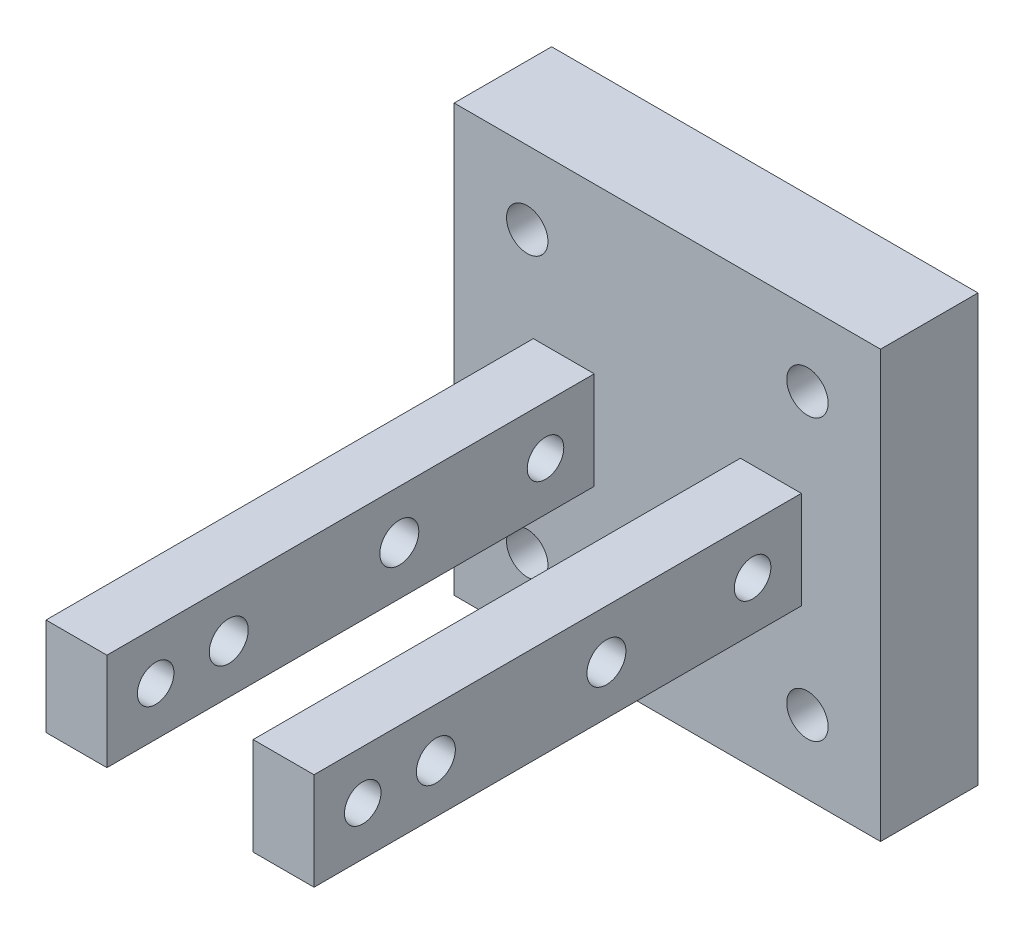
SolidWorks part; units mm, degrees
ref_plane "前视基准面" through (0, 0, 0) normal (0, 0, 1) x (1, 0, 0)
ref_plane "上视基准面" through (0, 0, 0) normal (0, 1, 0) x (1, 0, 0)
ref_plane "右视基准面" through (0, 0, 0) normal (1, 0, 0) x (0, 0, -1)
sketch "草图1" plane through (0, 0, 0) normal (0, 0, 1) x (1, 0, 0)
  line L0 (-10.8, 10.5686) -> (24.2, -24.4314) construction
  line L1 (-10.8, 10.5686) -> (24.2, 10.5686)
  line L2 (-10.8, 10.5686) -> (-10.8, -24.4314)
  line L3 (-10.8, -24.4314) -> (24.2, -24.4314)
  line L4 (24.2, 10.5686) -> (24.2, -24.4314)
  line L10 (-4.8, 4.5686) -> (18.2, -18.4314) construction
  line L11 (-4.8, -18.4314) -> (18.2, 4.5686) construction
  circle A0 centre (-4.8, 4.5686) radius 1.7
  circle A1 centre (18.2, 4.5686) radius 1.7
  circle A2 centre (-4.8, -18.4314) radius 1.7
  circle A3 centre (18.2, -18.4314) radius 1.7
  point P4 (6.7, -6.9314)
  dimension "D1" = 35
  dimension "D2" = 35
  dimension "D3" = 23
extrude "凸台-拉伸1" add sketch "草图1" along normal blind 8
sketch "草图2" plane through (0, 0, 8) normal (0, 0, 1) x (1, 0, 0)
  line L0 (6.7, 10.5686) -> (6.7, -24.4314) construction
  line L1 (24.2, 10.5686) -> (-10.8, 10.5686) construction
  line L2 (-10.8, -24.4314) -> (24.2, -24.4314) construction
  line L3 (-10.8, -6.9314) -> (24.2, -6.9314) construction
  line L4 (-10.8, 10.5686) -> (-10.8, -24.4314) construction
  line L5 (24.2, -24.4314) -> (24.2, 10.5686) construction
  line L6 (0.7, -6.9314) -> (12.7, -6.9314)
  line L7 (12.7, -2.9314) -> (12.7, -10.9314)
  line L8 (0.7, -2.9314) -> (0.7, -10.9314)
  line L10 (12.7, -2.9314) -> (17.7, -2.9314)
  line L11 (12.7, -2.9314) -> (12.7, -10.9314)
  line L12 (12.7, -10.9314) -> (17.7, -10.9314)
  line L13 (17.7, -2.9314) -> (17.7, -10.9314)
  line L14 (0.7, -2.9314) -> (-4.3, -2.9314)
  line L15 (0.7, -2.9314) -> (0.7, -10.9314)
  line L16 (0.7, -10.9314) -> (-4.3, -10.9314)
  line L17 (-4.3, -2.9314) -> (-4.3, -10.9314)
  point P15 (6.7, -6.9314)
  point P18 (12.7, -6.9314)
  point P21 (0.7, -6.9314)
  dimension "D1" = 12
  dimension "D2" = 8
  dimension "D3" = 8
  dimension "D4" = 5
  dimension "D5" = 5
extrude "凸台-拉伸2" add sketch "草图2" along normal blind 40 contours L14 L17 L16 L8 | L13 L10 L7 L12
sketch "草图3" plane through (17.7, 0, 0) normal (1, 0, 0) x (0, 0, -1)
  line L0 (-48, -6.9314) -> (-38, -6.9314) construction
  line L1 (-48, -2.9314) -> (-48, -10.9314) construction
  line L2 (-38, -6.9314) -> (-24, -6.9314) construction
  circle A0 centre (-38, -6.9314) radius 1.6
  circle A1 centre (-24, -6.9314) radius 1.6
  dimension "D2" = 14
  dimension "D1" = 10
extrude "切除-拉伸1" cut sketch "草图3" against normal blind 40
sketch "草图5" plane through (-4.3, 0, 0) normal (-1, 0, 0) x (0, 0, 1)
  line L0 (8, -6.9314) -> (48, -6.9314) construction
  line L1 (8, -2.9314) -> (8, -10.9314) construction
  line L2 (12, -6.9314) -> (44, -6.9314)
  circle A0 centre (12, -6.9314) radius 1.5
  circle A1 centre (44, -6.9314) radius 1.5
  point P7 (28, -6.9314)
  dimension "D1" = 40
  dimension "D2" = 32
extrude "切除-拉伸2" cut sketch "草图5" against normal blind 24 contours A0 L0 L2 | L0 A0 L2 | L2 L0 A1 | L0 L2 A1
